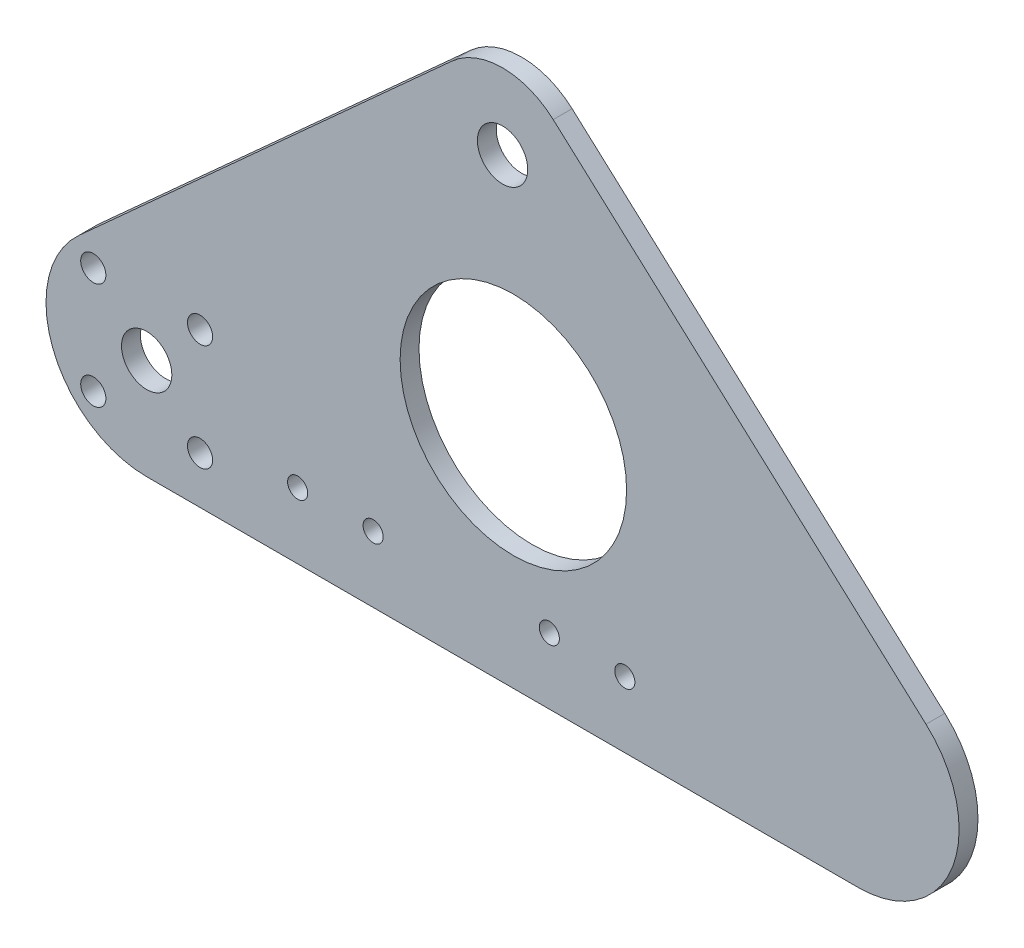
SolidWorks part; units mm, degrees
ref_plane "前视基准面" through (0, 0, 0) normal (0, 0, 1) x (1, 0, 0)
ref_plane "上视基准面" through (0, 0, 0) normal (0, 1, 0) x (1, 0, 0)
ref_plane "右视基准面" through (0, 0, 0) normal (1, 0, 0) x (0, 0, -1)
sketch "Model" plane through (0, 0, 0) normal (0, 0, 1) x (1, 0, 0)
  line L0 (-69.0181, -8.419) -> (-9.7661, 45.1832)
  line L1 (65.5867, -8.419) -> (6.3347, 45.1832)
  line L2 (-58.2843, -36.2843) -> (54.8528, -36.2843)
  circle A0 centre (5.7157, -25.7843) radius 1.6
  circle A1 centre (0, 0) radius 18
  circle A2 centre (-58.2843, -20.2843) radius 4
  circle A3 centre (-1.7157, 36.2843) radius 4
  circle A4 centre (-22.2843, -25.7843) radius 1.6
  circle A5 centre (-34.2843, -25.7843) radius 1.6
  circle A6 centre (17.7157, -25.7843) radius 1.6
  arc A7 (6.3347, 45.1832) -> (-9.7661, 45.1832) centre (-1.7157, 36.2843) ccw
  arc A8 (54.8528, -36.2843) -> (65.5867, -8.419) centre (54.8528, -20.2843) ccw
  arc A9 (-69.0181, -8.419) -> (-58.2843, -36.2843) centre (-58.2843, -20.2843) ccw
  circle A10 centre (-58.2843, -20.2843) radius 12 construction
  circle A53 centre (-66.7696, -11.799) radius 2
  circle A54 centre (-49.799, -11.799) radius 2
  circle A55 centre (-49.799, -28.7696) radius 2
  circle A56 centre (-66.7696, -28.7696) radius 2
  point P22 (0, 0)
  point P23 (0, 0)
  point P24 (0, 0)
  point P25 (0, 0)
  point P26 (0, 0)
  point P27 (0, 0)
  point P28 (0, 0)
  dimension "D1" = 8
  dimension "D2" = 24
  dimension "D3" = 4
  dimension "D4" = 4
  dimension "D5" = 4
  dimension "D6" = 4
extrude "凸台-拉伸1" add sketch "Model" along normal blind 3
